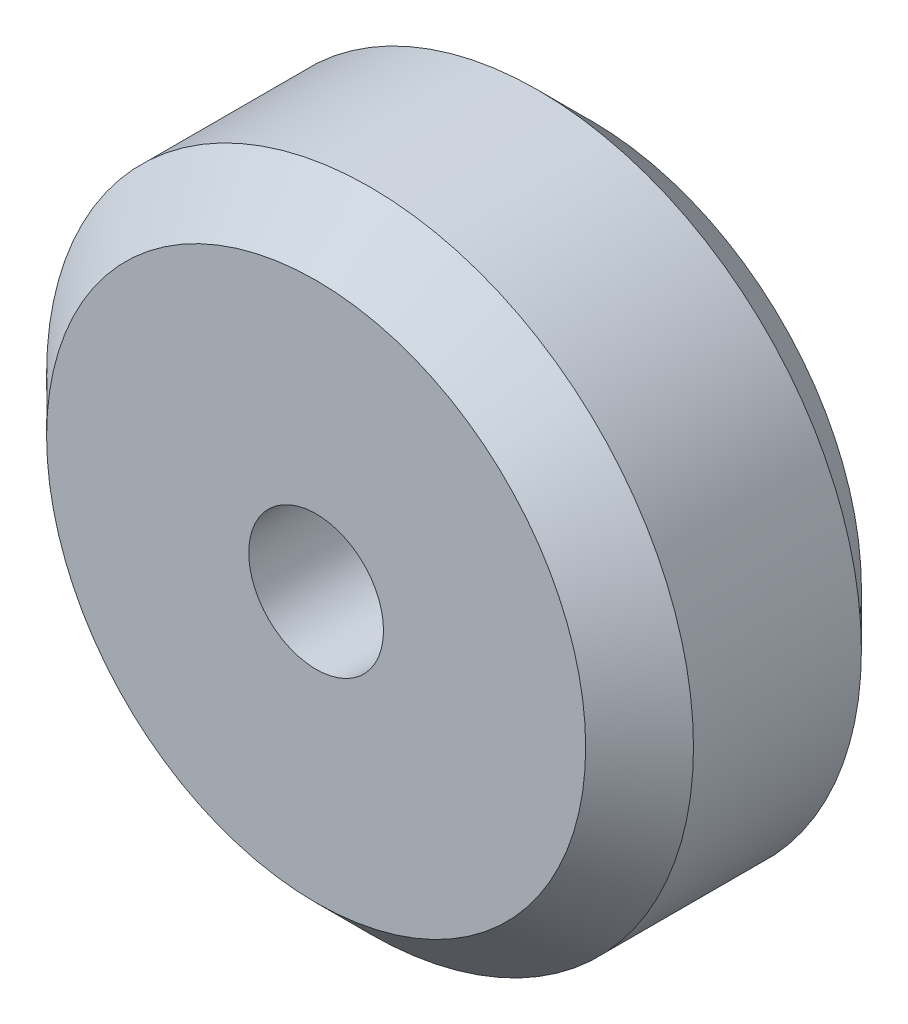
SolidWorks part; units mm, degrees
ref_plane "Front Plane" through (0, 0, 0) normal (0, 0, 1) x (1, 0, 0)
ref_plane "Top Plane" through (0, 0, 0) normal (0, 1, 0) x (1, 0, 0)
ref_plane "Right Plane" through (0, 0, 0) normal (1, 0, 0) x (0, 0, -1)
sketch "Sketch2" plane through (0, 0, 0) normal (0, 0, 1) x (1, 0, 0)
  circle A0 centre (0, 0) radius 12
  dimension "D1" = 24
extrude "Boss-Extrude1" add sketch "Sketch2" along normal blind 10.23
sketch "Sketch3" plane through (0, 0, 10.23) normal (0, 0, 1) x (1, 0, 0)
  circle A0 centre (0, 0) radius 2.5
  dimension "D1" = 5
extrude "Cut-Extrude1" cut sketch "Sketch3" against normal through all
chamfer "Chamfer1" distance 2 angle 45 1 edges at (12, 0, 10.23)
chamfer "Chamfer2" distance 2 angle 45 1 edges at (12, 0, 0)
